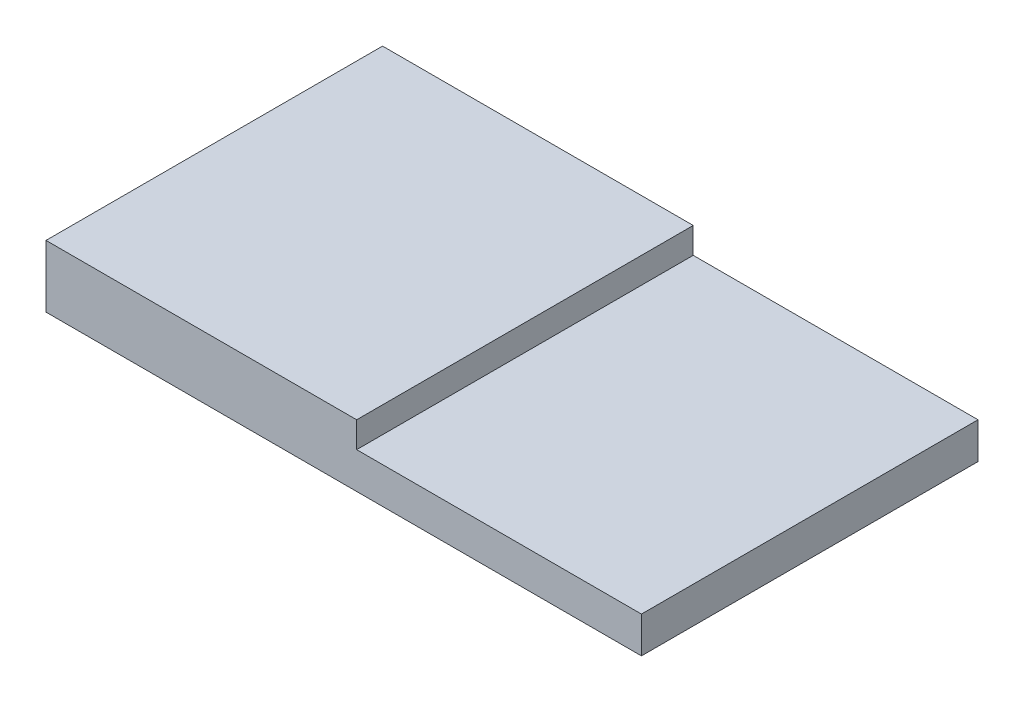
SolidWorks part; units mm, degrees
ref_plane "정면" through (0, 0, 0) normal (0, 0, 1) x (1, 0, 0)
ref_plane "윗면" through (0, 0, 0) normal (0, 1, 0) x (1, 0, 0)
ref_plane "우측면" through (0, 0, 0) normal (1, 0, 0) x (0, 0, -1)
sketch "스케치1" plane through (0, 0, 0) normal (0, 1, 0) x (1, 0, 0)
  line L1 (57.5, 32.5) -> (-57.5, 32.5)
  line L2 (57.5, 32.5) -> (57.5, -32.5)
  line L3 (57.5, -32.5) -> (-57.5, -32.5)
  line L4 (-57.5, 32.5) -> (-57.5, -32.5)
  line L5 (57.5, 32.5) -> (-57.5, -32.5) construction
  line L6 (57.5, -32.5) -> (-57.5, 32.5) construction
  point P0 (0, 0)
  dimension "D1" = 65
  dimension "D2" = 115
extrude "보스-돌출1" add sketch "스케치1" along normal blind 12
sketch "스케치3" plane through (0, 0, 0) normal (0, 0, 1) x (1, 0, 0)
  line L0 (-57.5, 12) -> (57.5, 12) construction
  line L1 (2.5, 12) -> (57.5, 12)
  line L2 (2.5, 12) -> (2.5, 7)
  line L3 (2.5, 7) -> (57.5, 7)
  line L4 (57.5, 12) -> (57.5, 7)
  line L5 (57.5, 12) -> (57.5, 0) construction
  line L6 (-57.5, 0) -> (57.5, 0) construction
  dimension "D1" = 7
  dimension "D2" = 55
extrude "컷-돌출1" cut sketch "스케치3" against normal through all both and the other way through all
